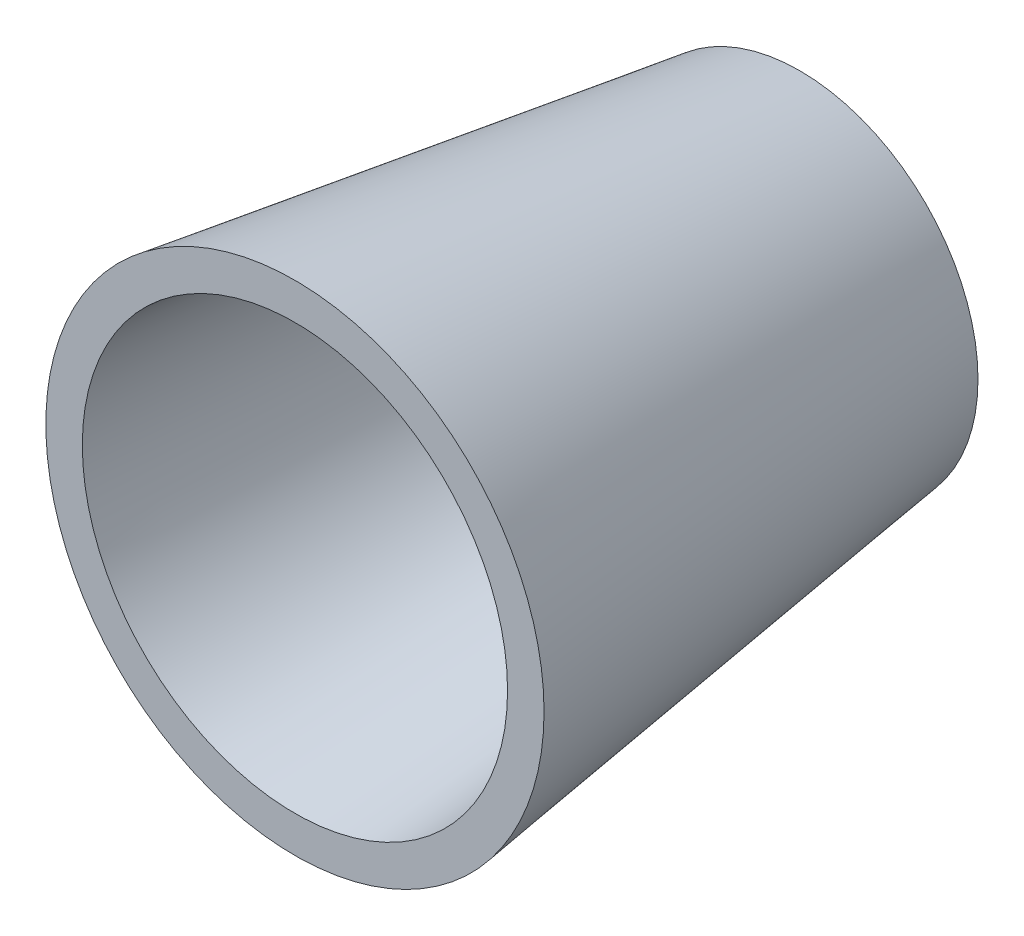
SolidWorks part; units mm, degrees
ref_plane "Front Plane" through (0, 0, 0) normal (0, 0, 1) x (1, 0, 0)
ref_plane "Top Plane" through (0, 0, 0) normal (0, 1, 0) x (1, 0, 0)
ref_plane "Right Plane" through (0, 0, 0) normal (1, 0, 0) x (0, 0, -1)
sketch "Sketch2" plane through (0, 0, 0) normal (0, 0, 1) x (1, 0, 0)
  circle A0 centre (0, 0) radius 52.9279
extrude "Boss-Extrude2" add sketch "Sketch2" along normal blind 150 draft 8 draft outward yes
sketch "Sketch6" plane through (0, 0, 0) normal (0, 0, -1) x (-1, 0, 0)
  circle A0 centre (0, 0) radius 36.8491
extrude "Cut-Extrude2" cut sketch "Sketch6" against normal blind 130
sketch "Sketch8" plane through (0, 0, 150) normal (0, 0, 1) x (1, 0, 0)
  circle A0 centre (0, 0) radius 63.1687
extrude "Cut-Extrude4" cut sketch "Sketch8" against normal blind 141 draft 5
